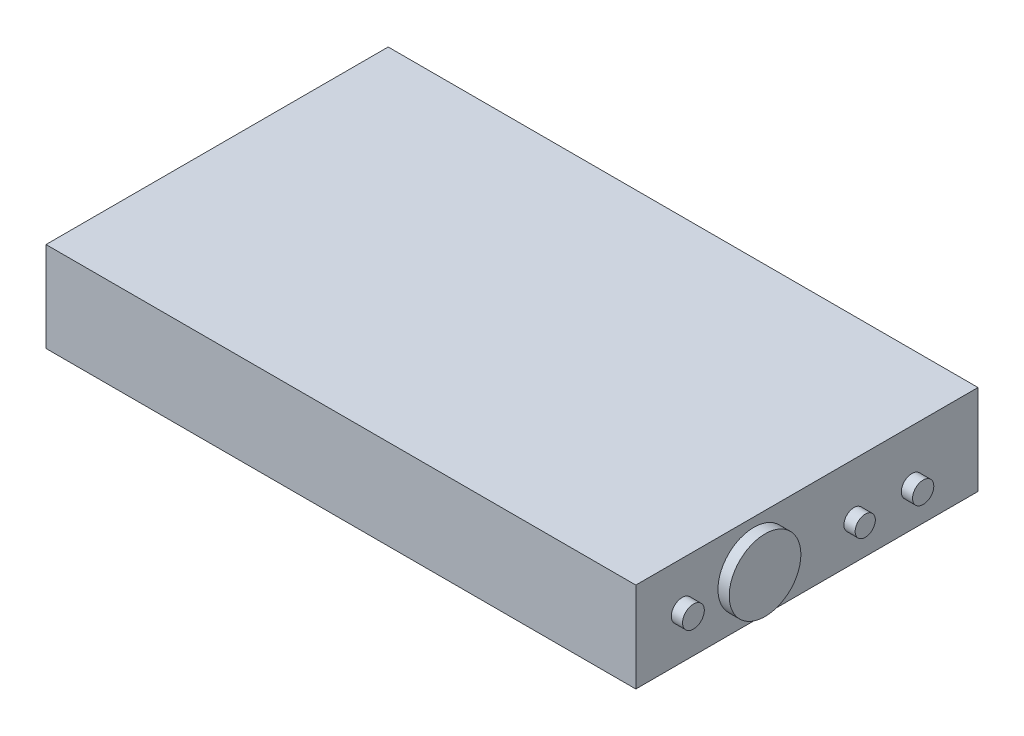
SolidWorks part; units mm, degrees
ref_plane "Front Plane" through (0, 0, 0) normal (0, 0, 1) x (1, 0, 0)
ref_plane "Top Plane" through (0, 0, 0) normal (0, 1, 0) x (1, 0, 0)
ref_plane "Right Plane" through (0, 0, 0) normal (1, 0, 0) x (0, 0, -1)
sketch "Sketch1" plane through (0, 0, 0) normal (0, 1, 0) x (1, 0, 0)
  line L1 (0, 0) -> (-332.74, 0)
  line L2 (0, 0) -> (0, -193.04)
  line L3 (0, -193.04) -> (-332.74, -193.04)
  line L4 (-332.74, 0) -> (-332.74, -193.04)
  dimension "D1" = 332.74
  dimension "D2" = 193.04
extrude "Boss-Extrude1" add sketch "Sketch1" along normal blind 50.8
sketch "Sketch2" plane through (0, 0, 0) normal (1, 0, 0) x (0, 0, -1)
  circle A0 centre (-126.4809, 25.5135) radius 20.2162
  circle A1 centre (-166.8828, 25.5135) radius 6.1326
  circle A2 centre (-69.9637, 21.4279) radius 5.6925
  circle A3 centre (-37.2791, 21.4279) radius 5.9924
extrude "Boss-Extrude2" add sketch "Sketch2" along normal blind 6.35
